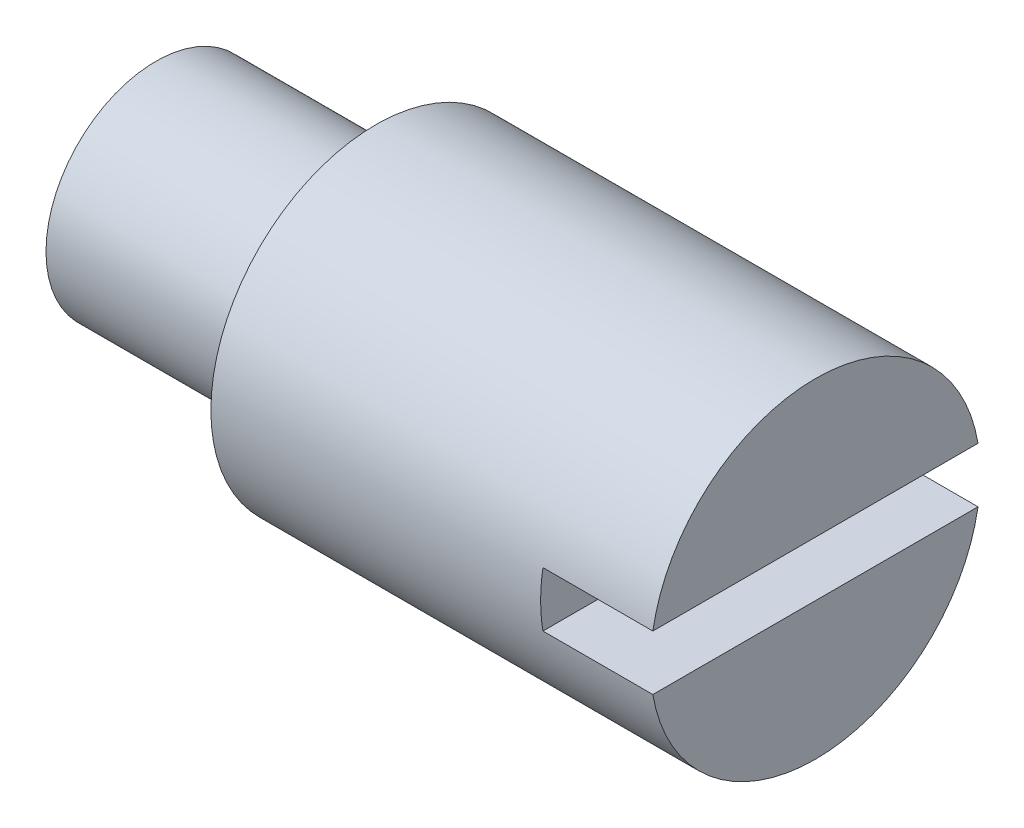
SolidWorks part; units mm, degrees
ref_plane "Front Plane" through (0, 0, 0) normal (0, 0, 1) x (1, 0, 0)
ref_plane "Top Plane" through (0, 0, 0) normal (0, 1, 0) x (1, 0, 0)
ref_plane "Right Plane" through (0, 0, 0) normal (1, 0, 0) x (0, 0, -1)
sketch "Sketch1" plane through (0, 0, 0) normal (0, 0, 1) x (1, 0, 0)
  line L0 (0, 0) -> (0, 2)
  line L1 (0, 2) -> (4, 2)
  line L2 (4, 2) -> (4, 3)
  line L3 (4, 3) -> (12, 3)
  line L4 (12, 3) -> (12, 0)
  line L7 (-2.8809, 0) -> (15.5773, 0) construction
  line L8 (0, 0) -> (12, 0)
  point P8 (12, 0.5)
  point P11 (12, 0.5)
  point P12 (12, 0)
  point P13 (15.5773, 0)
  point P14 (11.8526, 0)
  dimension "D1" = 2
  dimension "D2" = 12
  dimension "D4" = 4
  dimension "D5" = 3
revolve "Revolve1" add sketch "Sketch1" angle 360 about L7
sketch "Sketch2" plane through (0, 0, 0) normal (0, 0, 1) x (1, 0, 0)
  line L0 (12, -3) -> (12, 3) construction
  line L1 (10, -0.5) -> (12, -0.5)
  line L2 (10, -0.5) -> (10, 0.5)
  line L3 (10, 0.5) -> (12, 0.5)
  line L4 (12, -0.5) -> (12, 0.5)
  line L5 (10, -0.5) -> (12, 0.5) construction
  line L6 (10, 0.5) -> (12, -0.5) construction
  point P0 (11, 0)
  dimension "D1" = 1
  dimension "D2" = 2
extrude "Cut-Extrude1" cut sketch "Sketch2" against normal through all both and the other way through all
